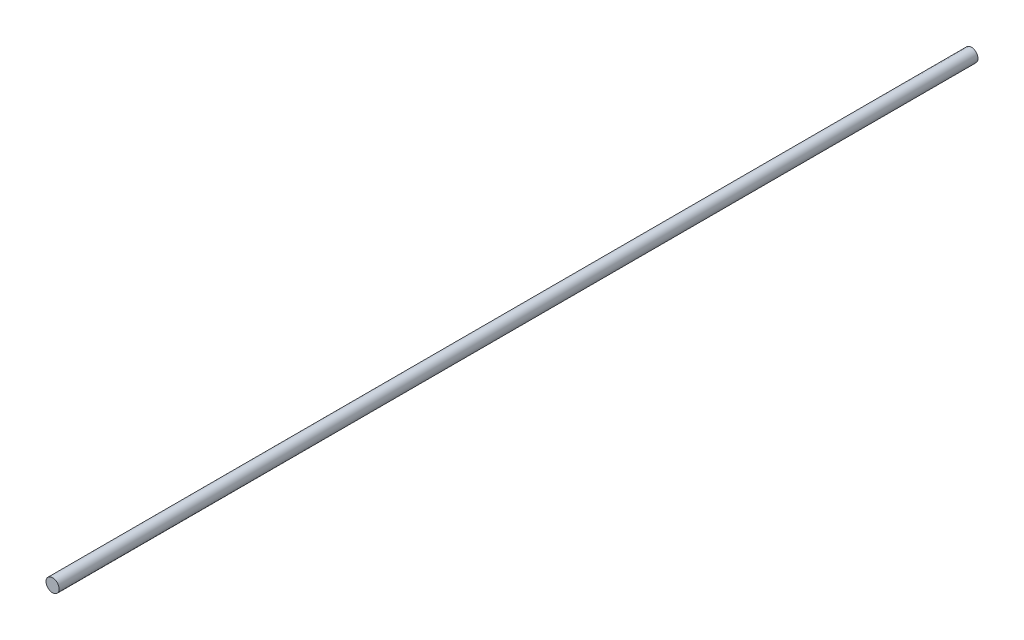
SolidWorks part; units mm, degrees
ref_plane "Plan de face" through (0, 0, 0) normal (0, 0, 1) x (1, 0, 0)
ref_plane "Plan de dessus" through (0, 0, 0) normal (0, 1, 0) x (1, 0, 0)
ref_plane "Plan de droite" through (0, 0, 0) normal (1, 0, 0) x (0, 0, -1)
sketch "Esquisse1" plane through (0, 0, 0) normal (0, 0, 1) x (1, 0, 0)
  circle A0 centre (0, 0) radius 3
  dimension "D1" = 6
extrude "Boss.-Extru.1" add sketch "Esquisse1" along normal blind 420
